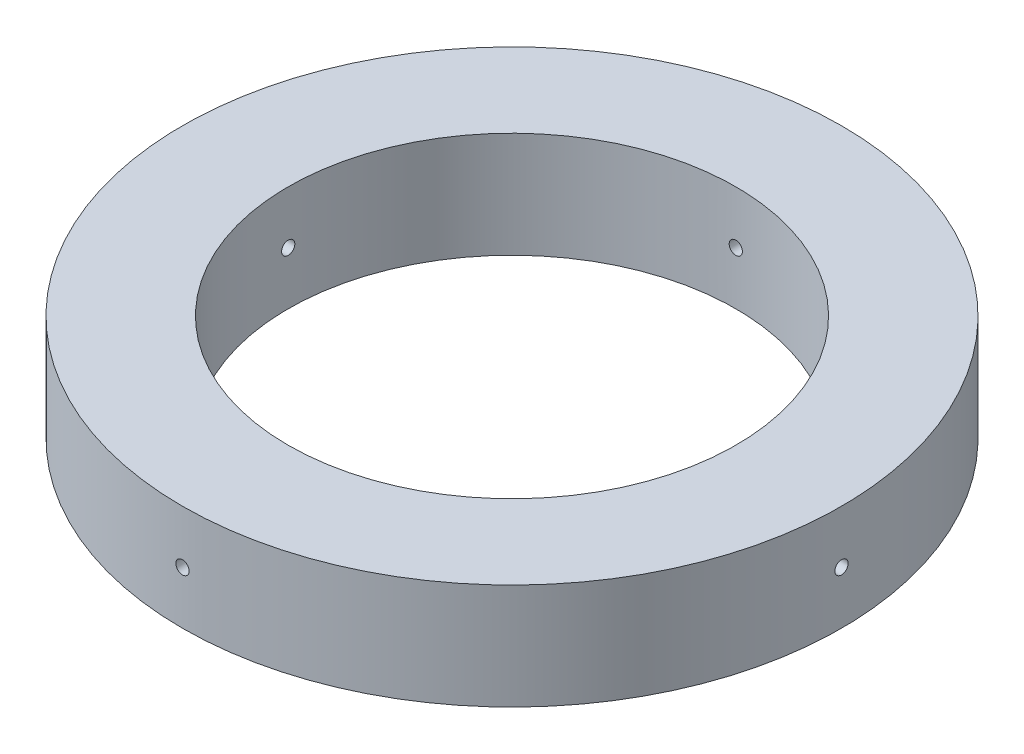
SolidWorks part; units mm, degrees
ref_plane "Front Plane" through (0, 0, 0) normal (0, 0, 1) x (1, 0, 0)
ref_plane "Top Plane" through (0, 0, 0) normal (0, 1, 0) x (1, 0, 0)
ref_plane "Right Plane" through (0, 0, 0) normal (1, 0, 0) x (0, 0, -1)
sketch "Croquis1" plane through (0, 0, 0) normal (0, 1, 0) x (1, 0, 0)
  circle A0 centre (0, 0) radius 42.36
  circle A1 centre (0, 0) radius 62.36
  dimension "D1" = 84.72
  dimension "D2" = 124.72
extrude "Saliente-Extruir1" add sketch "Croquis1" along normal blind 20
sketch "Croquis2" plane through (0, 0, 0) normal (0, 0, 1) x (1, 0, 0)
  circle A0 centre (0, 10) radius 1.25
  point P2 (0, 0)
  point P4 (0, 0)
  dimension "D2" = 2.5
  dimension "D1" = 10
extrude "Cortar-Extruir1" cut sketch "Croquis2" against normal up to surface (62.3475 mm away)
pattern_circular "MatrizC1" count 4 over 360 about axis through (0, 20, 0) along (0, 1, 0) of "Cortar-Extruir1"
equation "\"D2@Croquis1\"=84.72+20*2"
